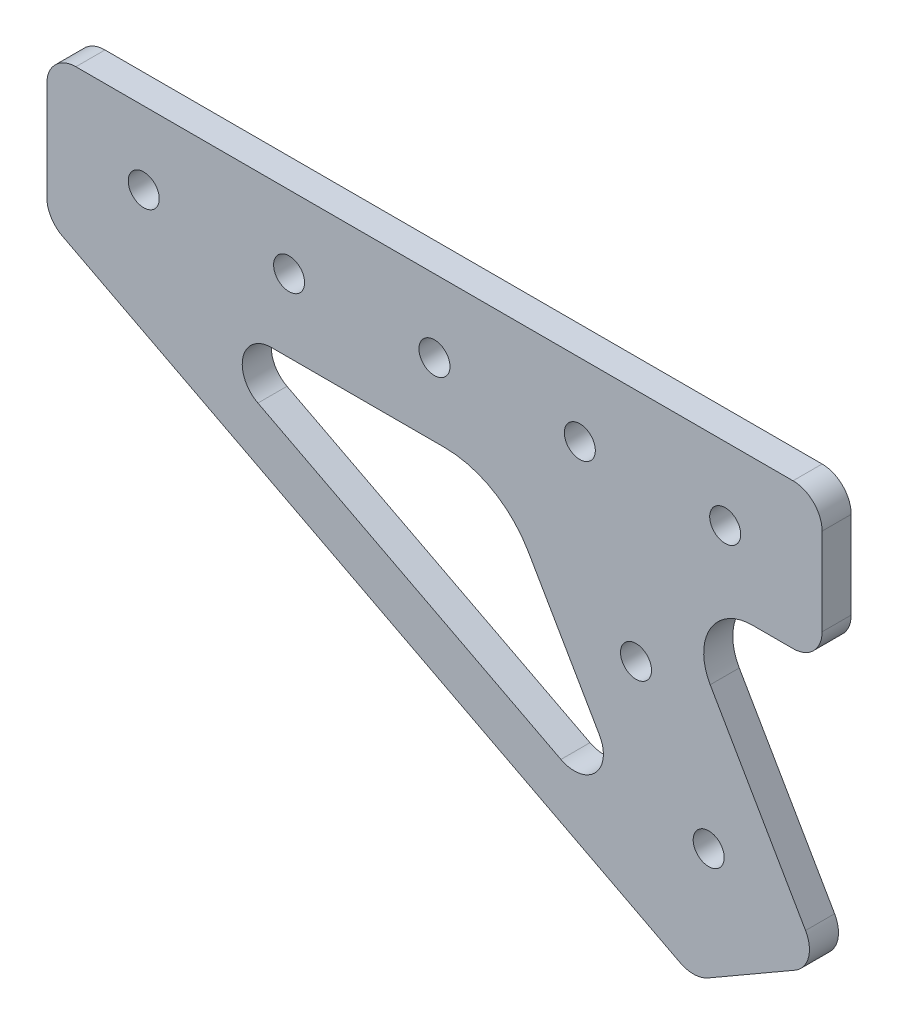
SolidWorks part; units mm, degrees
material "Hexcel AS4C (3000 丝)"
ref_plane "前视基准面" through (0, 0, 0) normal (0, 0, 1) x (1, 0, 0)
ref_plane "上视基准面" through (0, 0, 0) normal (0, 1, 0) x (1, 0, 0)
ref_plane "右视基准面" through (0, 0, 0) normal (1, 0, 0) x (0, 0, -1)
other "Configuration Table"
sketch "草图1" plane through (0, 0, 0) normal (0, 0, 1) x (1, 0, 0)
  line L0 (0, -15) -> (-15.878, -15)
  line L1 (-750, -15) -> (0, -15) construction
  line L2 (-80, -15) -> (-80, 0)
  line L4 (-80, 0) -> (0, 0)
  line L5 (0, 0) -> (0, -15)
  line L6 (-15.878, -15) -> (-0.2081, -42.141)
  line L7 (84.122, -188.2051) -> (-15.878, -15) construction
  line L8 (-0.2081, -42.141) -> (-13.1985, -49.641)
  line L9 (71.1316, -195.7051) -> (-28.8684, -22.5) construction
  line L10 (-17.8399, -41.6018) -> (-33.1985, -15)
  line L11 (-33.1985, -15) -> (-69.1387, -15)
  line L12 (-13.1985, -49.641) -> (-80, -15)
  line L13 (-17.8399, -41.6018) -> (-69.1387, -15)
  point P21 (-21.6739, -40.8243)
  dimension "D1" = 40
  dimension "D2" = 80
  dimension "D3" = 5
  dimension "D4" = 15
extrude "凸台-拉伸1" add sketch "草图1" along normal blind 3
fillet "圆角1" radius 5 1 edges at (-15.878, -15, 1.5)
fillet "圆角2" radius 10 1 edges at (-33.1985, -15, 1.5)
fillet "圆角3" radius 3 6 edges at (-80, 0, 1.5) (-0.2081, -42.141, 1.5) (0, 0, 1.5) (0, -15, 1.5) (-80, -15, 1.5) (-13.1985, -49.641, 1.5)
sketch "草图2" plane through (0, 0, 3) normal (0, 0, 1) x (1, 0, 0)
  line L0 (-11.7758, -48.8196) -> (-2.8062, -43.641) construction
  line L2 (-11.7033, -37.2308) -> (-19.2033, -24.2404) construction
  line L3 (-30.3117, -20) -> (-17.8399, -41.6018) construction
  line L4 (0, -12) -> (0, -3) construction
  line L5 (-3, 0) -> (-77, 0) construction
  line L6 (-1.7081, -39.5429) -> (-11.5478, -22.5) construction
  circle A0 centre (-11.7033, -37.2308) radius 1.6
  circle A1 centre (-19.2033, -24.2404) radius 1.6
  circle A2 centre (-10, -7.5) radius 1.6
  circle A3 centre (-25, -7.5) radius 1.6
  circle A4 centre (-40, -7.5) radius 1.6
  circle A5 centre (-55, -7.5) radius 1.6
  circle A6 centre (-70, -7.5) radius 1.6
  dimension "D3" = 3.2
  dimension "D4" = 3.2
  dimension "D1" = 15
  dimension "D2" = 10
  dimension "D5" = 10
  dimension "D6" = 15
  dimension "D7" = 15
  dimension "D8" = 15
  dimension "D9" = 15
  dimension "D10" = 7.5
  dimension "D11" = 7.5
extrude "切除-拉伸1" cut sketch "草图2" against normal blind 3
fillet "圆角4" radius 3 2 edges at (-69.1387, -15, 1.5) (-17.8399, -41.6018, 1.5)
